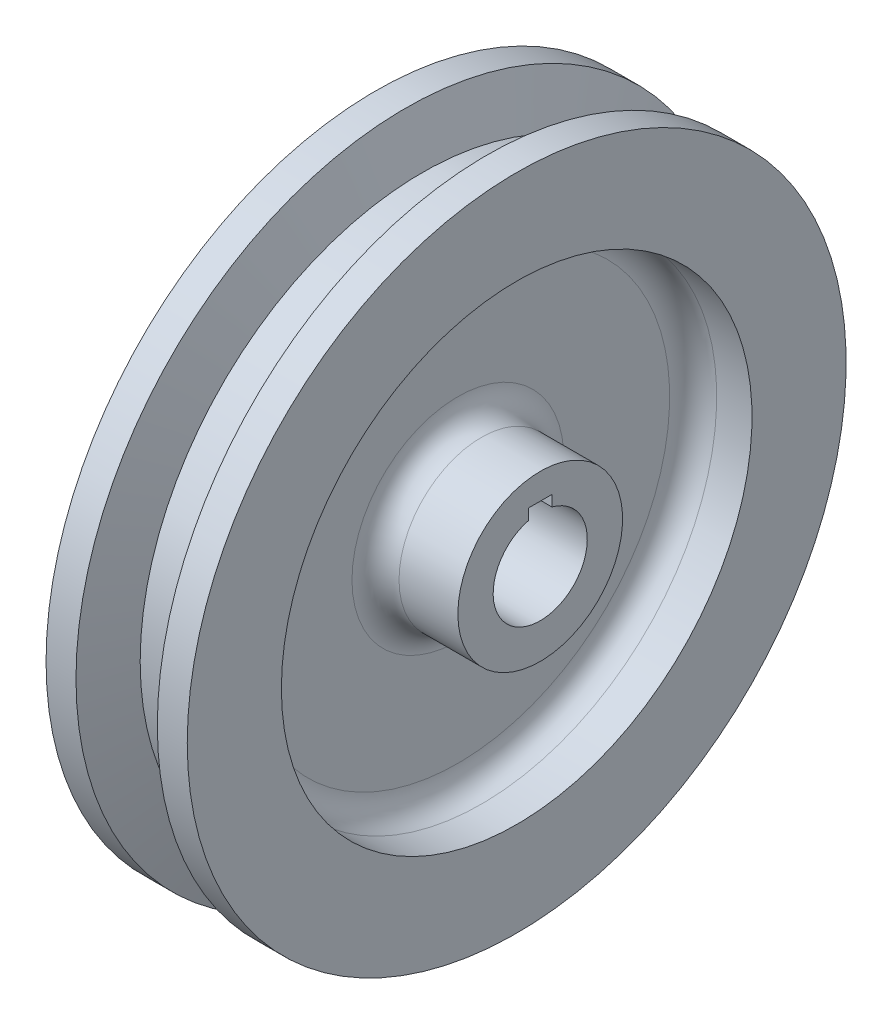
SolidWorks part; units mm, degrees
material "Cast Carbon Steel"
ref_plane "Front Plane" through (0, 0, 0) normal (0, 0, 1) x (1, 0, 0)
ref_plane "Top Plane" through (0, 0, 0) normal (0, 1, 0) x (1, 0, 0)
ref_plane "Right Plane" through (0, 0, 0) normal (1, 0, 0) x (0, 0, -1)
sketch "Sketch1" plane through (0, 0, 0) normal (0, 0, 1) x (1, 0, 0)
  line L0 (-25.4, 0) -> (25.4, 0)
  line L16 (25.4, 0) -> (25.4, 22.225)
  line L17 (-25.4, 0) -> (-25.4, 22.225)
  line L18 (-25.4, 22.225) -> (-3.175, 22.225)
  line L19 (25.4, 22.225) -> (3.175, 22.225)
  line L20 (-3.175, 22.225) -> (-3.175, 63.5)
  line L21 (3.175, 22.225) -> (3.175, 63.5)
  line L22 (-3.175, 63.5) -> (-19.05, 63.5)
  line L23 (-19.05, 63.5) -> (-19.05, 88.9)
  line L24 (-19.05, 88.9) -> (-10.9724, 88.9)
  line L26 (6.35, 76.2) -> (-6.35, 76.2)
  line L28 (10.9724, 88.9) -> (19.05, 88.9)
  line L29 (19.05, 88.9) -> (19.05, 63.5)
  line L30 (19.05, 63.5) -> (3.175, 63.5)
  line L33 (6.35, 76.2) -> (10.9724, 88.9)
  line L34 (-6.35, 76.2) -> (-10.9724, 88.9)
  point P11 (0, 76.2)
  point P12 (0, 0)
  point P15 (-15.0112, 88.9)
  dimension "D1" = 22.225
  dimension "D2" = 50.8
  dimension "D3" = 6.35
  dimension "D4" = 12.7
  dimension "D5" = 88.9
  dimension "D6" = 12.7
  dimension "D7" = 40
  dimension "D8" = 38.1
  dimension "D9" = 63.5
revolve "Revolve1" add sketch "Sketch1" angle 360 about L0
fillet "Fillet1" radius 6.35 4 edges at (3.175, 0, 63.5) (3.175, 0, 22.225) (-3.175, 0, 63.5) (-3.175, 0, 22.225)
sketch "Sketch3" plane through (-25.4, 0, 0) normal (-1, 0, 0) x (0, 0, 1)
  line L0 (-3.175, 15.24) -> (3.175, 15.24)
  line L1 (-3.175, 15.24) -> (-3.175, 12.2967)
  line L2 (3.175, 15.24) -> (3.175, 12.2967)
  arc A0 (-3.175, 12.2967) -> (3.175, 12.2967) centre (0, 0) ccw
  point P7 (0, 15.24)
  dimension "D1" = 25.4
  dimension "D2" = 6.35
  dimension "D3" = 15.24
extrude "Cut-Extrude1" cut sketch "Sketch3" against normal through all
